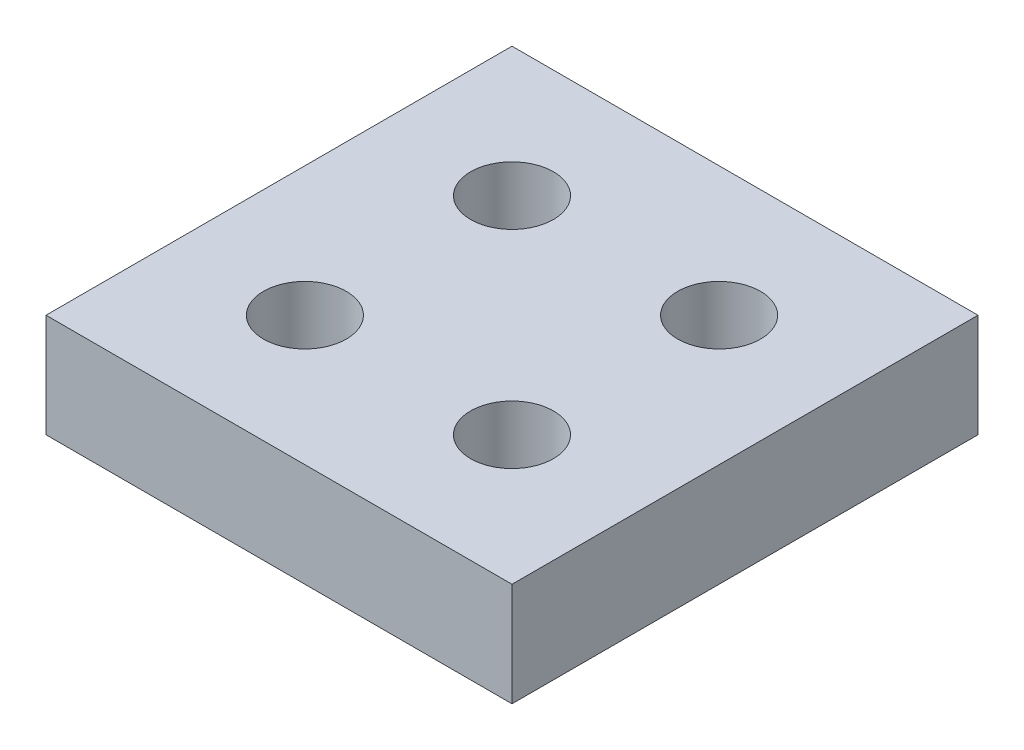
SolidWorks part; units mm, degrees
ref_plane "前视基准面" through (0, 0, 0) normal (0, 0, 1) x (1, 0, 0)
ref_plane "上视基准面" through (0, 0, 0) normal (0, 1, 0) x (1, 0, 0)
ref_plane "右视基准面" through (0, 0, 0) normal (1, 0, 0) x (0, 0, -1)
sketch "草图1" plane through (0, 0, 0) normal (0, 1, 0) x (1, 0, 0)
  line L1 (-2.25, -2.25) -> (2.25, -2.25)
  line L2 (-2.25, -2.25) -> (-2.25, 2.25)
  line L3 (-2.25, 2.25) -> (2.25, 2.25)
  line L4 (2.25, -2.25) -> (2.25, 2.25)
  line L5 (-2.25, -2.25) -> (2.25, 2.25) construction
  line L6 (-2.25, 2.25) -> (2.25, -2.25) construction
  circle A0 centre (-1, 1) radius 0.4
  circle A1 centre (1, 1) radius 0.4
  circle A2 centre (1, -1) radius 0.4
  circle A3 centre (-1, -1) radius 0.4
  point P0 (0, 0)
  point P17 (0, 0)
  dimension "D3" = 0.8
  dimension "D1" = 4.5
  dimension "D2" = 45
  dimension "D5" = 1
  dimension "D4" = 4
extrude "凸台-拉伸1" add sketch "草图1" along normal blind 1
